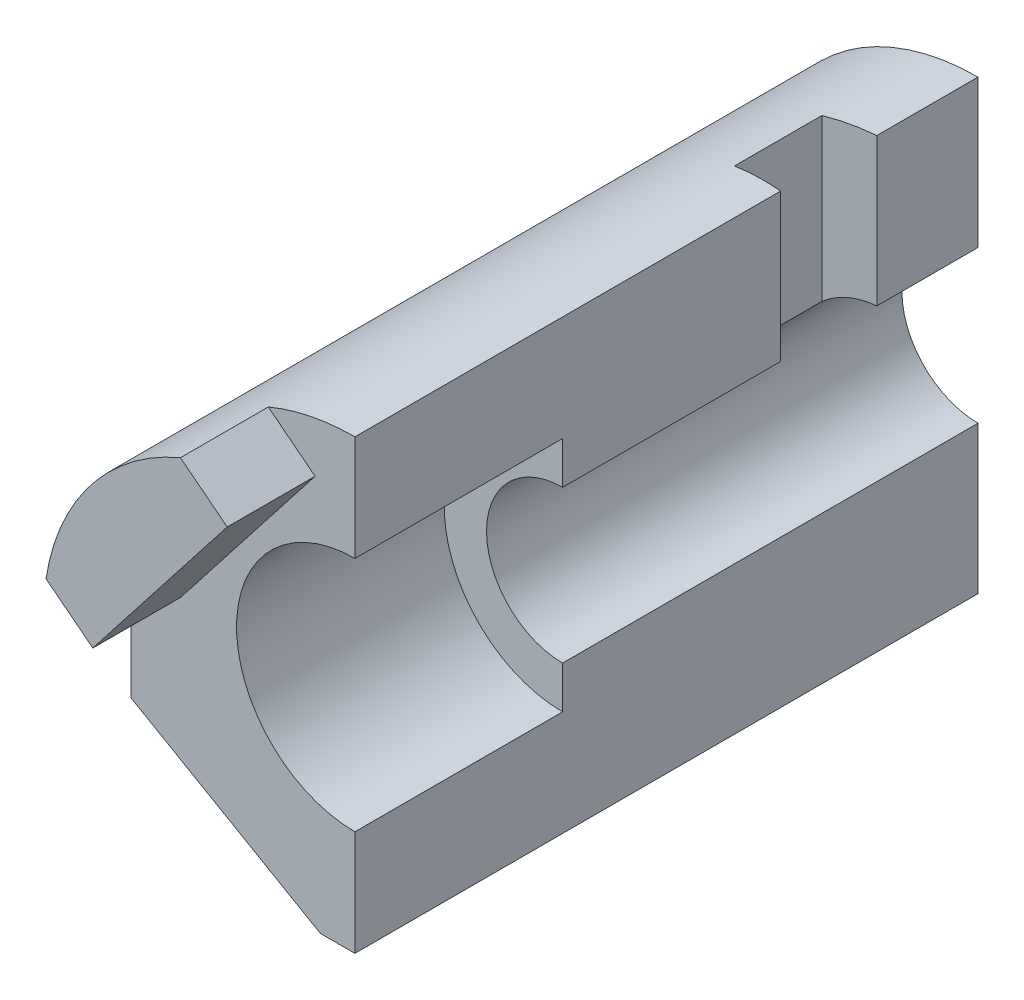
SolidWorks part; units mm, degrees
material "1060 Alloy"
ref_plane "Front Plane" through (0, 0, 0) normal (0, 0, 1) x (1, 0, 0)
ref_plane "Top Plane" through (0, 0, 0) normal (0, 1, 0) x (1, 0, 0)
ref_plane "Right Plane" through (0, 0, 0) normal (1, 0, 0) x (0, 0, -1)
sketch "Sketch1" plane through (0, 0, 0) normal (0, 0, 1) x (1, 0, 0)
  line L0 (28.3536, 84) -> (28.3536, 40.9919)
  line L4 (112.3536, 0) -> (112.3536, 55.425)
  line L5 (28.3536, 40.9919) -> (99.3536, 0)
  line L6 (99.3536, 0) -> (112.3536, 0)
  line L7 (112.3536, 112.575) -> (112.3536, 168)
  arc A0 (112.3536, 112.575) -> (112.3536, 55.425) centre (112.3536, 84) ccw
  arc A1 (112.3536, 168) -> (28.3536, 84) centre (112.3536, 84) ccw
  dimension "D5" = 84
  dimension "D6" = 28.575
  dimension "D1" = 84
  dimension "D2" = 30
  dimension "D3" = 13
  dimension "D4" = 84
extrude "Boss-Extrude2" add sketch "Sketch1" along normal blind 234
sketch "Sketch3" plane through (0, 0, 234) normal (0, 0, 1) x (1, 0, 0)
  line L0 (112.3536, 112.575) -> (112.3536, 55.425) construction
  line L1 (112.3536, 112.575) -> (112.3536, 168) construction
  arc A0 (112.3536, 112.575) -> (112.3536, 55.425) centre (112.3536, 84) ccw construction
  circle A1 centre (112.3536, 84) radius 44.45
  dimension "D1" = 88.9
extrude "Cut-Extrude1" cut sketch "Sketch3" against normal blind 78
sketch "Sketch4" plane through (0, 0, 234) normal (0, 0, 1) x (1, 0, 0)
  line L2 (99.3536, 0) -> (112.3536, 0) construction
  line L3 (46.9229, 83.0903) -> (97.4072, 147.7072)
  line L4 (46.9229, 83.0903) -> (29.339, 96.8284)
  line L5 (97.4072, 147.7072) -> (79.8232, 161.4453)
  arc A0 (112.3536, 168) -> (28.3536, 84) centre (112.3536, 84) ccw construction
  arc A1 (29.339, 96.8284) -> (79.8232, 161.4453) centre (112.3536, 84) cw
  point P14 (72.1651, 115.3987)
  dimension "D2" = 82
  dimension "D4" = 38
extrude "Boss-Extrude3" add sketch "Sketch4" along normal blind 33
ref_plane "Plane1" through (0, 168, 0) normal (0, 1, 0) x (1, 0, 0)
sketch "Sketch5" plane through (0, 168, 0) normal (0, 1, 0) x (1, 0, 0)
  line L0 (112.3536, -234) -> (112.3536, 0) construction
  line L2 (112.3536, -38) -> (112.3536, -74.1075)
  line L4 (93.3536, -39.6623) -> (93.3536, -72.4452)
  line L5 (93.3536, -39.6623) -> (112.3536, -38)
  line L6 (93.3536, -72.4452) -> (112.3536, -74.1075)
  dimension "D1" = 38
extrude "Cut-Extrude3" cut sketch "Sketch5" against normal up to next
equation "\"A\"= 234.00"
equation "\"B\"= 117.00"
equation "\"C\"= 84"
equation "\"D\"= 5rad"
